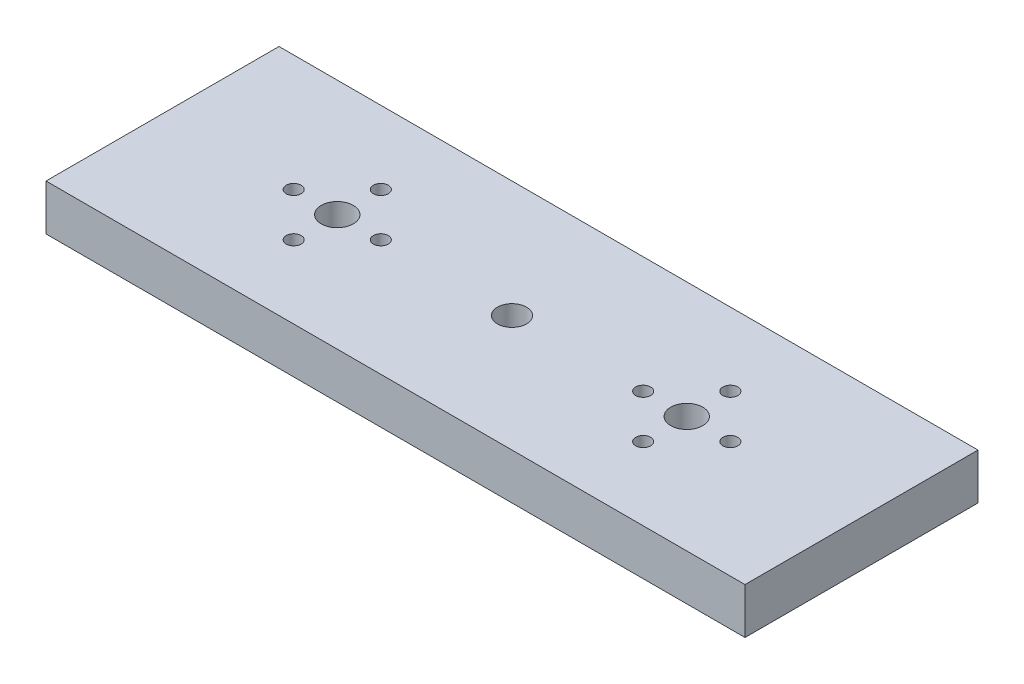
SolidWorks part; units mm, degrees
material "FEA Aluminum"
ref_plane "Front Plane" through (0, 0, 0) normal (0, 0, 1) x (1, 0, 0)
ref_plane "Top Plane" through (0, 0, 0) normal (0, 1, 0) x (1, 0, 0)
ref_plane "Right Plane" through (0, 0, 0) normal (1, 0, 0) x (0, 0, -1)
sketch "Sketch2" plane through (0, 0, 0) normal (0, 1, 0) x (1, 0, 0)
  line L1 (152.4, 50.8) -> (-152.4, 50.8)
  line L2 (152.4, 50.8) -> (152.4, -50.8)
  line L3 (152.4, -50.8) -> (-152.4, -50.8)
  line L4 (-152.4, 50.8) -> (-152.4, -50.8)
  line L5 (152.4, 50.8) -> (-152.4, -50.8) construction
  line L6 (152.4, -50.8) -> (-152.4, 50.8) construction
  circle A0 centre (0, 0) radius 6.35
  circle A1 centre (-76.2, 0) radius 7
  circle A2 centre (76.2, 0) radius 7
  point P0 (0, 0)
  dimension "D3" = 12.7
  dimension "D4" = 14
  dimension "D1" = 304.8
  dimension "D2" = 101.6
  dimension "D5" = 76.2
  dimension "D6" = 76.2
extrude "Boss-Extrude1" add sketch "Sketch2" along normal blind 20
sketch "Sketch3" plane through (0, 20, 0) normal (0, 1, 0) x (1, 0, 0)
  circle A0 centre (-76.2, 0) radius 19 construction
  circle A1 centre (-76.2, 19) radius 3.25
  dimension "D1" = 38
  dimension "D2" = 6.5
extrude "Cut-Extrude1" cut sketch "Sketch3" against normal through all
pattern_circular "CirPattern1" count 4 over 360 about axis through (-76.2, 0, 0) along (0, 1, 0) of "Cut-Extrude1"
pattern_linear "LPattern1" count 2 spacing 152.4 along (1, 0, 0) of "CirPattern1", "Cut-Extrude1"
equation "\"Length\"= 304.8"
equation "\"Width\"= 101.6"
equation "\"t\"= 20"
equation "\"Spacing\"= 152.4"
equation "\"Offset\"= 76.2"
equation "\"D1@Sketch2\"=\"Length\""
equation "\"D6@Sketch2\"=\"Offset\""
equation "\"D5@Sketch2\"=\"Offset\""
